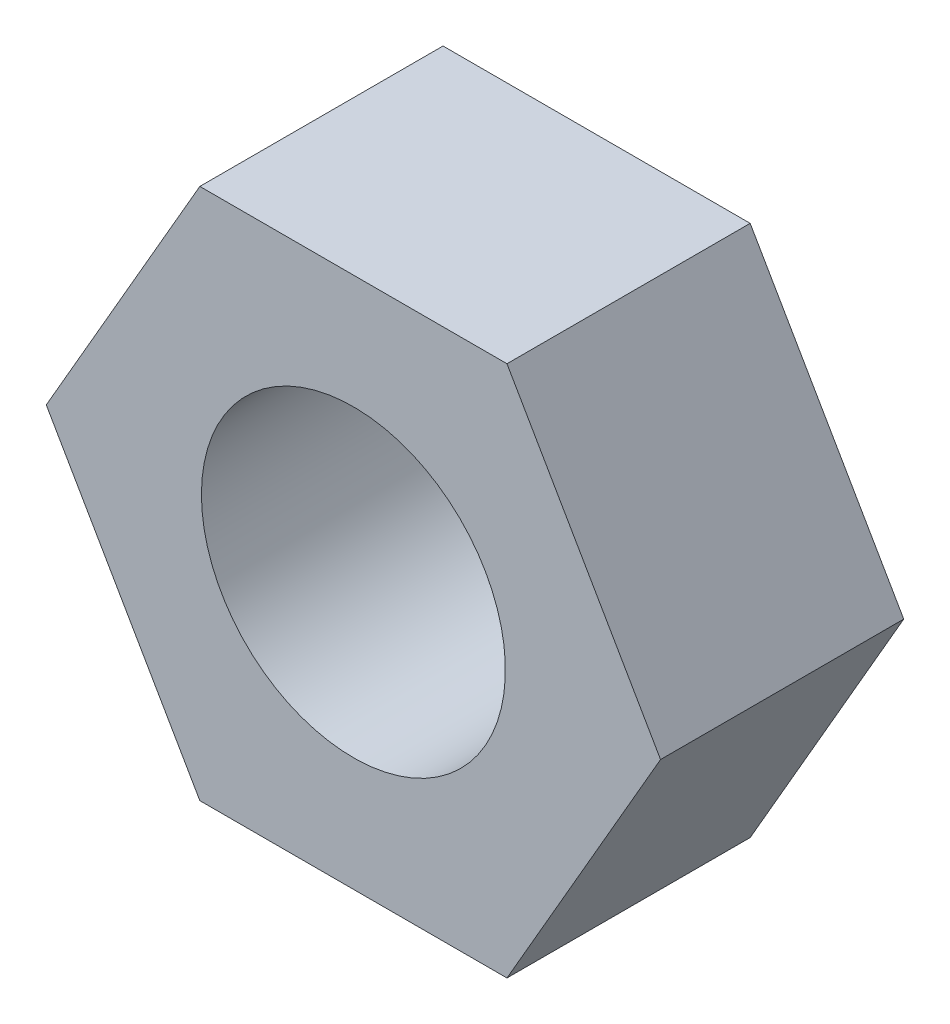
SolidWorks part; units mm, degrees
ref_plane "Front Plane" through (0, 0, 0) normal (0, 0, 1) x (1, 0, 0)
ref_plane "Top Plane" through (0, 0, 0) normal (0, 1, 0) x (1, 0, 0)
ref_plane "Right Plane" through (0, 0, 0) normal (1, 0, 0) x (0, 0, -1)
sketch "Sketch2" plane through (0, 0, 0) normal (0, 0, 1) x (1, 0, 0)
  line L1 (4.0415, 0) -> (2.0207, 3.5)
  line L2 (2.0207, 3.5) -> (-2.0207, 3.5)
  line L3 (-2.0207, 3.5) -> (-4.0415, 0)
  line L4 (-4.0415, 0) -> (-2.0207, -3.5)
  line L5 (-2.0207, -3.5) -> (2.0207, -3.5)
  line L6 (2.0207, -3.5) -> (4.0415, 0)
  circle A0 centre (0, 0) radius 3.5 construction
  dimension "D1" = 7
extrude "Boss-Extrude1" add sketch "Sketch2" along normal blind 3.2
sketch "Sketch3" plane through (0, 0, 0) normal (0, 0, -1) x (-1, 0, 0)
  circle A0 centre (0, 0) radius 2
  dimension "D1" = 4
extrude "Cut-Extrude1" cut sketch "Sketch3" against normal blind 3.2
